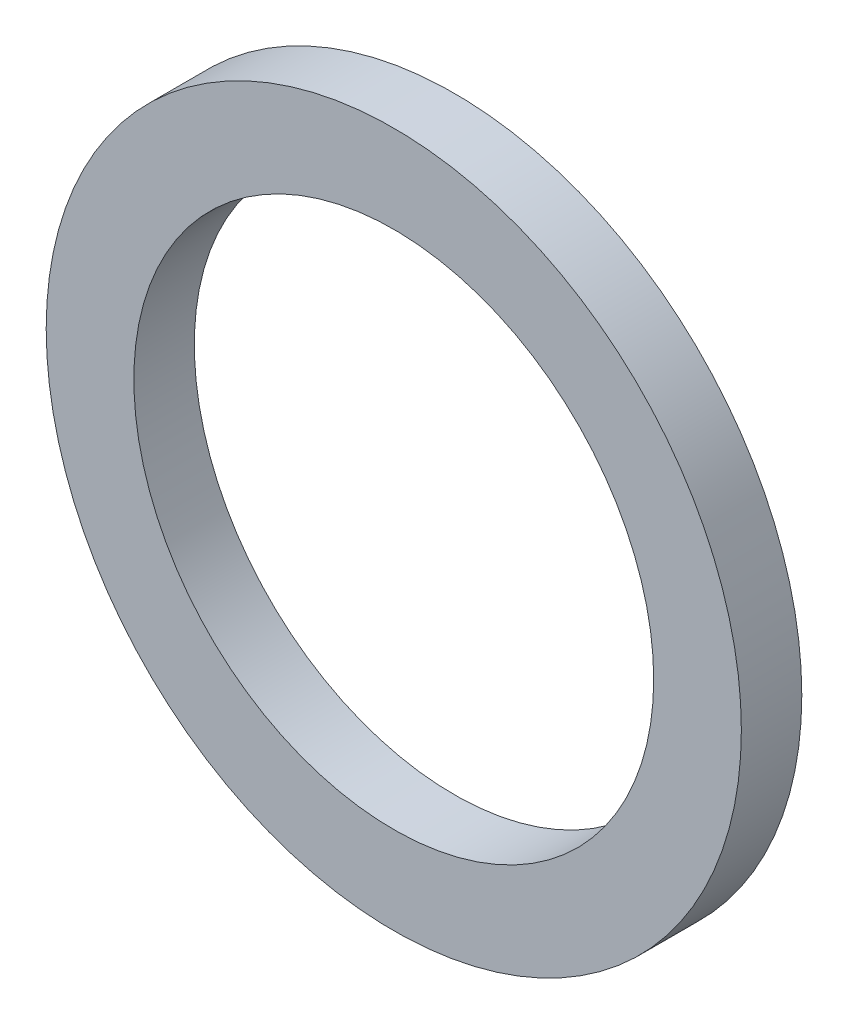
SolidWorks part; units mm, degrees
material "Сталь 3 ГОСТ 535-88"
ref_plane "Спереди" through (0, 0, 0) normal (0, 0, 1) x (1, 0, 0)
ref_plane "Сверху" through (0, 0, 0) normal (0, 1, 0) x (1, 0, 0)
ref_plane "Справа" through (0, 0, 0) normal (1, 0, 0) x (0, 0, -1)
sketch "Эскиз1" plane through (0, 0, 0) normal (0, 0, 1) x (1, 0, 0)
  circle A0 centre (0, 0) radius 11.5
  circle A1 centre (0, 0) radius 8.6
  dimension "D1" = 17.2
  dimension "D2" = 23
extrude "Бобышка-Вытянуть1" add sketch "Эскиз1" along normal blind 2
